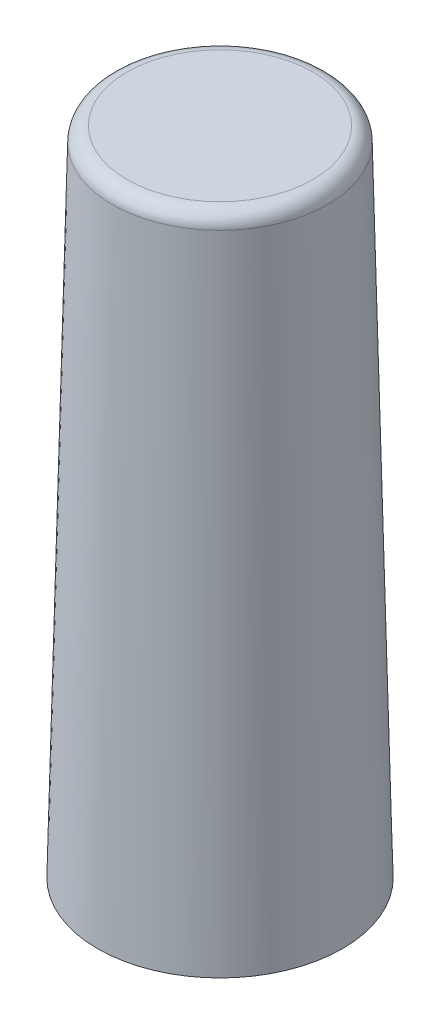
SolidWorks part; units mm, degrees
ref_plane "前视基准面" through (0, 0, 0) normal (0, 0, 1) x (1, 0, 0)
ref_plane "上视基准面" through (0, 0, 0) normal (0, 1, 0) x (1, 0, 0)
ref_plane "右视基准面" through (0, 0, 0) normal (1, 0, 0) x (0, 0, -1)
sketch "Sketch1" plane through (0, 0, 0) normal (1, 0, 0) x (0, 0, -1)
  line L0 (0, 0) -> (0, 130) construction
  line L1 (0, 130) -> (-22, 130) construction
  line L2 (0, 0) -> (-22.9995, 0) construction
  line L3 (-22, 130) -> (-25, 0)
  line L4 (0, 133) -> (-16.1976, 133)
  line L5 (-22, 130) -> (-21.9984, 130.0692)
  line L6 (-18.9992, 133) -> (-16.1976, 133)
  line L7 (0, 131) -> (-16.1976, 131)
  line L8 (-18.9992, 131) -> (-16.1976, 131)
  line L9 (-20.0005, 129.9539) -> (-19.9989, 130.0231)
  line L10 (-20.0005, 129.9539) -> (-22.8841, 5)
  line L11 (0, 133) -> (0, 131)
  line L12 (0, 0) -> (-16, 0) construction
  line L13 (-16, 0) -> (-16, 22.2973) construction
  line L14 (-22.8841, 5) -> (-16, 5)
  line L15 (-16, 5) -> (-16, 0)
  line L18 (-16, 0) -> (-25, 0)
  line L19 (-20.0005, 129.9539) -> (-23.0005, -0.0461) construction
  arc A0 (-21.9984, 130.0692) -> (-18.9992, 133) centre (-18.9992, 130) cw
  arc A1 (-19.9989, 130.0231) -> (-18.9992, 131) centre (-18.9992, 130) cw
  dimension "D5" = 3
  dimension "D1" = 22
  dimension "D2" = 25
  dimension "D3" = 130
  dimension "D4" = 3
  dimension "D7" = 16
  dimension "D8" = 5
  dimension "D6" = 2
revolve "Revolve1" add sketch "Sketch1" angle 360 about L0
sketch "Sketch6" plane through (0, 0, 0) normal (0, -1, 0) x (1, 0, 0)
  line L0 (0, 16) -> (0, 25) construction
  circle A0 centre (0, 0) radius 25 construction
  circle A1 centre (0, 0) radius 16 construction
  circle A2 centre (0, 0) radius 25 construction
  circle A3 centre (0, 0) radius 20.5 construction
  circle A4 centre (0, 20.5) radius 4
  circle A5 centre (17.7535, -10.25) radius 4
  circle A6 centre (-17.7535, -10.25) radius 4
  point P9 (0, 20.5)
  dimension "D1" = 3
extrude "Boss-Extrude2" add sketch "Sketch6" against normal up to body separate body
sketch "Sketch7" plane through (0, 0, 0) normal (0, -1, 0) x (1, 0, 0)
  circle A0 centre (0, 20.5) radius 2
  circle A1 centre (17.7535, -10.25) radius 2
  circle A2 centre (-17.7535, -10.25) radius 2
extrude "Cut-Extrude2" cut sketch "Sketch7" against normal blind 5
ref_plane "Plane1" through (0, 48, 0) normal (0, -1, 0) x (-1, 0, 0)
sketch "Sketch8" plane through (0, 48, 0) normal (0, -1, 0) x (-1, 0, 0)
  circle A0 centre (0, 0) radius 19
extrude "Cut-Extrude4" cut sketch "Sketch8" against normal up to surface (83 mm away) up to face at (0, 131, 0)
